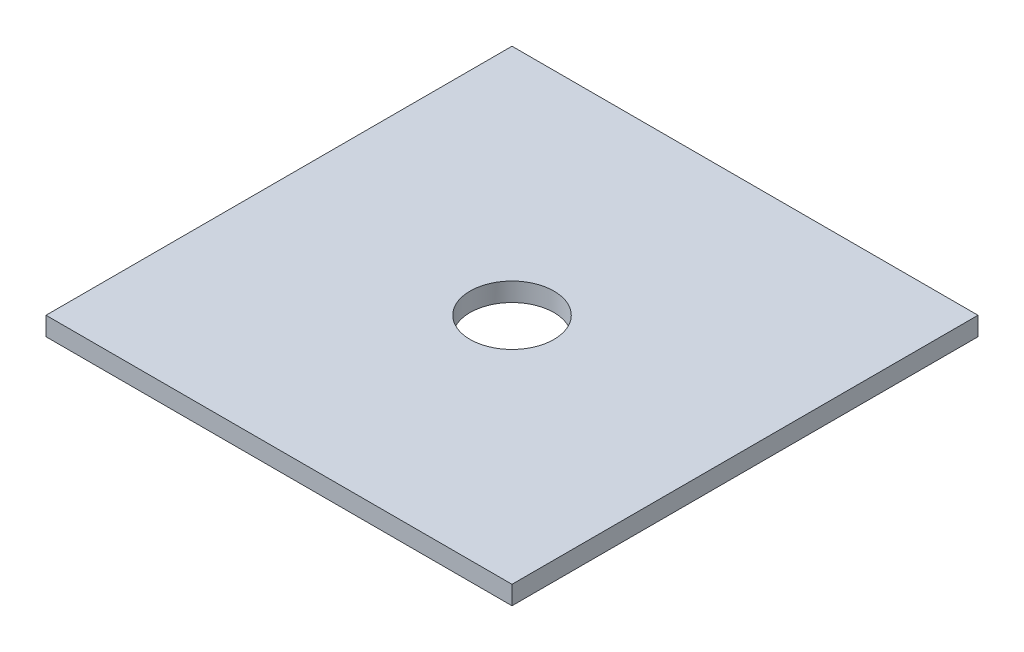
SolidWorks part; units mm, degrees
material "Chapa F.F 1020 - 2 mm"
ref_plane "Plano frontal" through (0, 0, 0) normal (0, 0, 1) x (1, 0, 0)
ref_plane "Plano superior" through (0, 0, 0) normal (0, 1, 0) x (1, 0, 0)
ref_plane "Plano direito" through (0, 0, 0) normal (1, 0, 0) x (0, 0, -1)
sketch "Esboço2" plane through (0, 0, 0) normal (0, 1, 0) x (1, 0, 0)
  line L1 (25, 25) -> (-25, 25)
  line L2 (25, 25) -> (25, -25)
  line L3 (25, -25) -> (-25, -25)
  line L4 (-25, 25) -> (-25, -25)
  line L5 (25, 25) -> (-25, -25) construction
  line L6 (25, -25) -> (-25, 25) construction
  point P0 (0, 0)
  dimension "D1" = 50
  dimension "D2" = 50
extrude "Ressalto-extrusão1" add sketch "Esboço2" along normal blind 2
hole_wizard "Furo com folga de M81" positions "Esboço4" profile "Esboço3" hole size "M8" standard "ISO"
sketch "Esboço4" plane through (0, 2, 0) normal (0, 1, 0) x (1, 0, 0)
  point P0 (0, 0)
sketch "Esboço3" plane through (0, 2, 0) normal (1, 0, 0) x (0, 0, 1)
  line L0 (0, 0) -> (0, 12.7039)
  line L1 (0, 12.7039) -> (4.5, 10)
  line L2 (4.5, 10) -> (4.5, 0)
  line L5 (4.5, 0) -> (0, 0)
  line L10 (0, 12.7039) -> (-4.5, 10) construction
  line L11 (0, -6.35) -> (0, 107.95) construction
  dimension "Hole Dia." = 9
  dimension "Hole Depth" = 10
  dimension "Drill Angle" = 118
